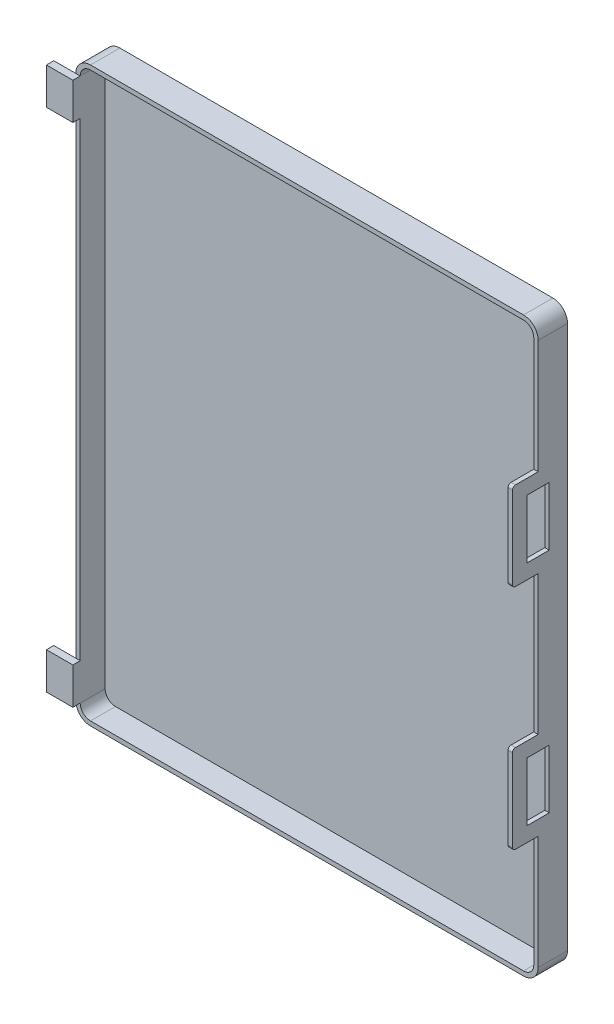
SolidWorks part; units mm, degrees
ref_plane "Front Plane" through (0, 0, 0) normal (0, 0, 1) x (1, 0, 0)
ref_plane "Top Plane" through (0, 0, 0) normal (0, 1, 0) x (1, 0, 0)
ref_plane "Right Plane" through (0, 0, 0) normal (1, 0, 0) x (0, 0, -1)
sketch "Sketch1" plane through (0, 0, 0) normal (0, 0, 1) x (1, 0, 0)
  line L0 (0, 0) -> (5.7686, 0) construction
  line L1 (0, 0) -> (0, 5.7871) construction
  line L3 (-14.75, 19.5) -> (14.75, 19.5)
  line L4 (-15.75, 18.5) -> (-15.75, -18.5)
  line L5 (-14.75, -19.5) -> (14.75, -19.5)
  line L6 (15.75, 18.5) -> (15.75, -18.5)
  arc A0 (14.75, -19.5) -> (15.75, -18.5) centre (14.75, -18.5) ccw
  arc A1 (-15.75, -18.5) -> (-14.75, -19.5) centre (-14.75, -18.5) ccw
  arc A2 (-14.75, 19.5) -> (-15.75, 18.5) centre (-14.75, 18.5) ccw
  arc A3 (14.75, 19.5) -> (15.75, 18.5) centre (14.75, 18.5) cw
  point P11 (15.75, -19.5)
  point P16 (-15.75, 19.5)
  point P19 (15.75, 19.5)
  dimension "D3" = 1
  dimension "D1" = 31.5
  dimension "D2" = 39
extrude "Boss-Extrude1" add sketch "Sketch1" along normal blind 2
shell "Shell1" thickness 0.3
sketch "Sketch2" plane through (15.75, 0, 0) normal (1, 0, 0) x (0, 0, -1)
  line L0 (-2, 0) -> (0, 0) construction
  line L1 (-2, -18.5) -> (-2, 18.5) construction
  line L2 (-1, 0) -> (-1, 7.75) construction
  line L3 (-1, 0) -> (-1, -7.75) construction
  line L4 (-1, -7.75) -> (-0.3813, -7.75) construction
  line L5 (-1, 7.75) -> (-2, 7.75) construction
  line L6 (-2, 7.75) -> (-2, 8.8233) construction
  line L7 (-3.75, 10.75) -> (-0.25, 10.75)
  line L8 (-2.75, 9.75) -> (-1.25, 9.75)
  line L9 (-2.75, 9.75) -> (-2.75, 5.75)
  line L10 (-2.75, 5.75) -> (-1.25, 5.75)
  line L11 (-1.25, 9.75) -> (-1.25, 5.75)
  line L12 (-0.25, 10.75) -> (-0.25, 4.75)
  line L13 (-3.75, 4.75) -> (-0.25, 4.75)
  line L14 (-3.75, 10.75) -> (-3.75, 4.75)
  line L15 (-1, 8.75) -> (-1, 8.75)
  line L16 (-1, 8.75) -> (-1, 8.8233)
  dimension "D1" = 7.75
  dimension "D2" = 7.75
  dimension "D3" = 1.5
  dimension "D4" = 4
  dimension "D5" = 1
extrude "Boss-Extrude2" add sketch "Sketch2" against normal blind 0.3
mirror "Mirror1" about plane through (0, 0, 0) normal (0, 1, 0) of "Boss-Extrude2"
sketch "Sketch3" plane through (15.75, 0, 0) normal (1, 0, 0) x (0, 0, -1)
  line L0 (-2, 9.75) -> (-1.25, 9.75)
  line L1 (-2, 5.75) -> (-1.25, 5.75)
  line L2 (-1.25, 5.75) -> (-1.25, 9.75)
  line L3 (-2, 9.75) -> (-2, 5.75)
  line L5 (-2, -5.75) -> (-1.25, -5.75)
  line L6 (-1.25, -5.75) -> (-1.25, -9.75)
  line L7 (-2, -9.75) -> (-1.25, -9.75)
  line L8 (-2, -9.75) -> (-2, -5.75)
  dimension "D1" = 0.75
extrude "Cut-Extrude1" cut sketch "Sketch3" against normal blind 0.3
fillet "Fillet1" radius 0.2 4 edges at (15.6, -10.75, 3.75) (15.6, -4.75, 3.75) (15.6, 4.75, 3.75) (15.6, 10.75, 3.75)
sketch "Sketch5" plane through (-15.75, 0, 0) normal (-1, 0, 0) x (0, 0, 1)
  line L0 (2, 18.5) -> (1.5, 18.5)
  line L1 (2, 18.5) -> (0, 18.5) construction
  line L2 (1.5, 18.5) -> (1.5, 16)
  line L3 (1.5, 16) -> (2, 16)
  line L4 (2, 18.5) -> (2, -18.5) construction
  line L5 (2, 16) -> (2, 18.5)
  line L6 (2, -18.5) -> (1.5, -18.5)
  line L7 (2, -18.5) -> (0, -18.5) construction
  line L8 (1.5, -18.5) -> (1.5, -16)
  line L9 (1.5, -16) -> (2, -16)
  line L10 (2, -16) -> (2, -18.5)
  dimension "D1" = 0.5
  dimension "D2" = 2.5
  dimension "D3" = 2.5
sketch "Sketch6" plane through (0, 0, 2) normal (0, 0, 1) x (1, 0, 0)
  line L6 (-17.25, -18.5) -> (-15.75, -18.5)
  line L7 (-17.25, -18.5) -> (-17.25, -16)
  line L8 (-17.25, -16) -> (-15.75, -16)
  line L9 (-17.25, 16) -> (-15.75, 16)
  line L10 (-17.25, 16) -> (-17.25, 18.5)
  line L11 (-17.25, 18.5) -> (-15.75, 18.5)
  line L12 (-15.75, -16) -> (-15.45, -16)
  line L13 (-15.75, 16) -> (-15.45, 16)
  line L14 (-15.45, 18.5) -> (-15.45, -18.5) construction
  line L15 (-15.45, 16) -> (-15.45, 18.5)
  line L16 (-15.45, 18.5) -> (-15.75, 18.5)
  line L17 (-15.45, -16) -> (-15.45, -18.5)
  line L18 (-15.45, -18.5) -> (-15.75, -18.5)
  arc A0 (-15.45, -18.5) -> (-14.75, -19.2) centre (-14.75, -18.5) ccw construction
  arc A1 (-15.45, -18.5) -> (-14.75, -19.2) centre (-14.75, -18.5) ccw construction
extrude "Boss-Extrude4" add sketch "Sketch6" along normal blind 0.5
